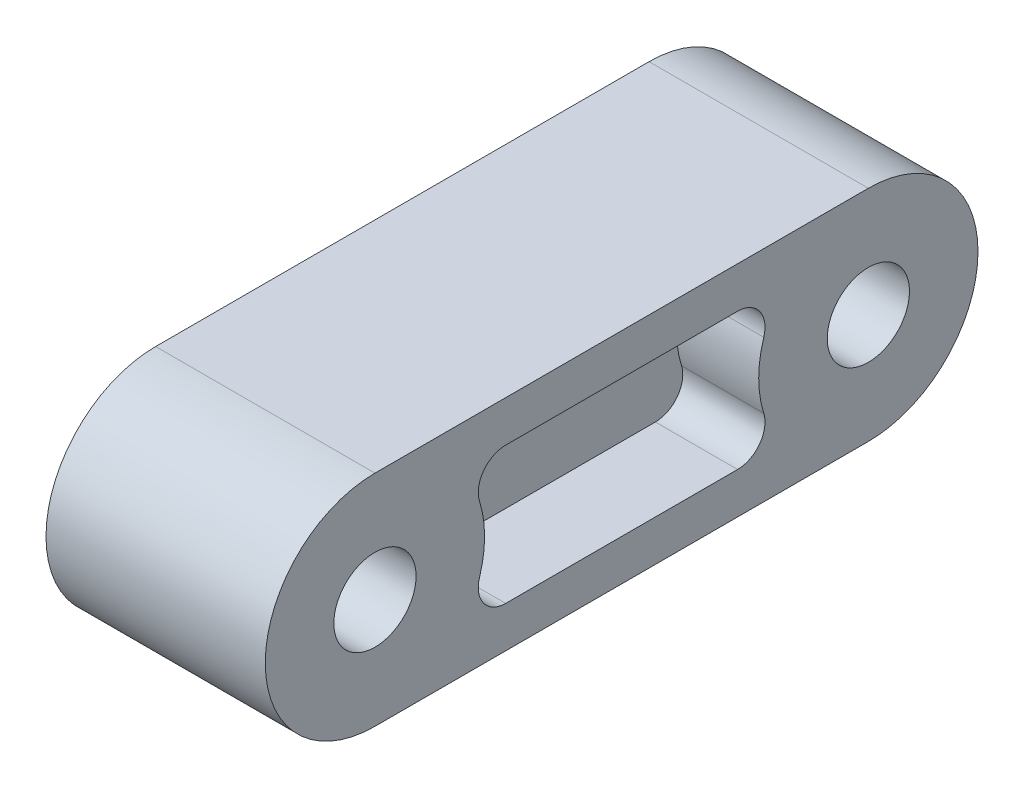
SolidWorks part; units mm, degrees
ref_plane "前视基准面" through (0, 0, 0) normal (0, 0, 1) x (1, 0, 0)
ref_plane "上视基准面" through (0, 0, 0) normal (0, 1, 0) x (1, 0, 0)
ref_plane "右视基准面" through (0, 0, 0) normal (1, 0, 0) x (0, 0, -1)
sketch "草图1" plane through (0, 0, 0) normal (1, 0, 0) x (0, 0, -1)
  line L0 (0, 0) -> (18, 0) construction
  line L1 (0, 0) -> (18, 0) construction
  line L2 (0, 4) -> (18, 4)
  line L3 (0, -4) -> (18, -4)
  circle A0 centre (0, 0) radius 1.5
  circle A1 centre (18, 0) radius 1.5
  arc A2 (0, 4) -> (0, -4) centre (0, 0) ccw
  arc A3 (18, -4) -> (18, 4) centre (18, 0) ccw
  point P5 (9, 0)
  dimension "D2" = 3
  dimension "D3" = 4
  dimension "D1" = 18
extrude "凸台-拉伸1" add sketch "草图1" along normal mid plane 8
sketch "草图2" plane through (4, 0, 0) normal (1, 0, 0) x (0, 0, -1)
  line L4 (0, -2.5) -> (18, -2.5)
  line L5 (18, 2.5) -> (0, 2.5)
  line L6 (3.1225, -2.5) -> (14.8775, -2.5)
  line L7 (14.8775, 2.5) -> (3.1225, 2.5)
  arc A2 (3.1225, -2.5) -> (3.1225, 2.5) centre (0, 0) ccw
  arc A3 (14.8775, 2.5) -> (14.8775, -2.5) centre (18, 0) ccw
  arc A4 (0, 2.5) -> (0, -2.5) centre (0, 0) ccw
  arc A5 (18, -2.5) -> (18, 2.5) centre (18, 0) ccw
  arc A8 (18, -4) -> (18, 4) centre (18, 0) ccw construction
  dimension "D1" = 1.5
extrude "切除-拉伸1" cut sketch "草图2" against normal blind 3
mirror "镜向1" about plane through (0, 0, 0) normal (1, 0, 0) of "切除-拉伸1"
fillet "圆角1" radius 1 8 edges at (-2.5, -2.5, -3.1225) (-2.5, 2.5, -3.1225) (-2.5, 2.5, -14.8775) (-2.5, -2.5, -14.8775) (2.5, 2.5, -14.8775) (2.5, -2.5, -3.1225) (2.5, -2.5, -14.8775) (2.5, 2.5, -3.1225)
